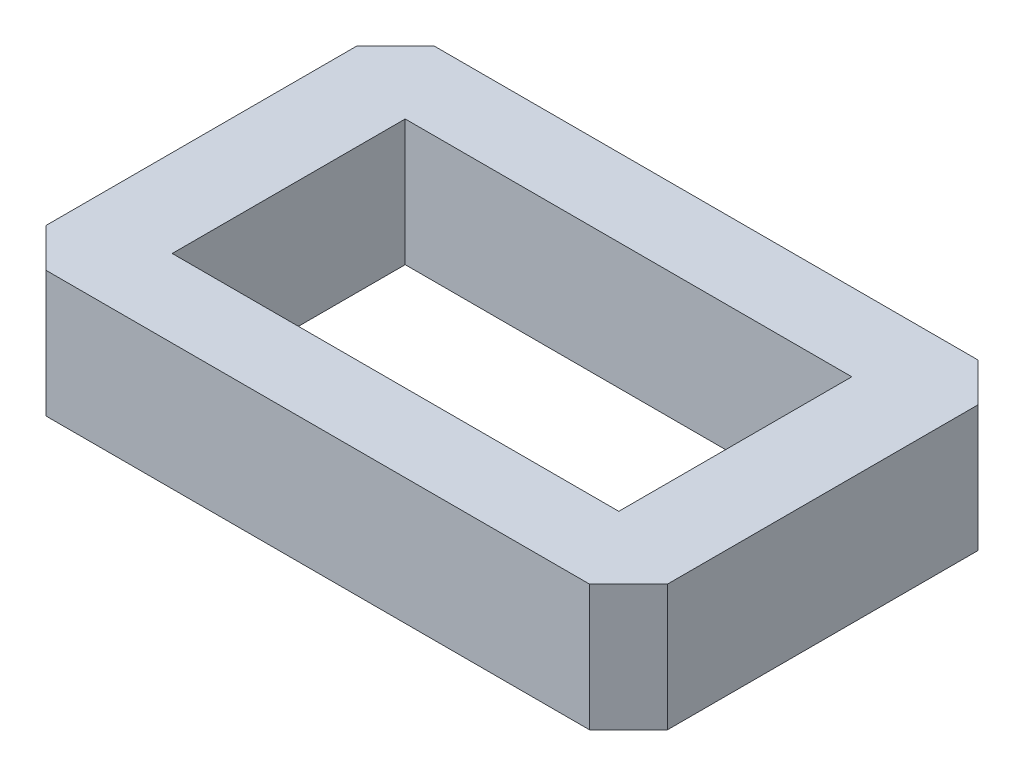
SolidWorks part; units mm, degrees
ref_plane "Front Plane" through (0, 0, 0) normal (0, 0, 1) x (1, 0, 0)
ref_plane "Top Plane" through (0, 0, 0) normal (0, 1, 0) x (1, 0, 0)
ref_plane "Right Plane" through (0, 0, 0) normal (1, 0, 0) x (0, 0, -1)
sketch "Sketch1" plane through (0, 0, 0) normal (0, 1, 0) x (1, 0, 0)
  line L1 (0, 0) -> (32, 0)
  line L2 (0, 0) -> (0, 20)
  line L3 (0, 20) -> (32, 20)
  line L4 (32, 0) -> (32, 20)
  dimension "D1" = 20
  dimension "D2" = 32
extrude "Boss-Extrude1" add sketch "Sketch1" along normal blind 6.5
sketch "Sketch2" plane through (0, 6.5, 0) normal (0, 1, 0) x (1, 0, 0)
  line L0 (16, 20) -> (16, 0)
  line L1 (32, 20) -> (0, 20) construction
  line L2 (0, 0) -> (32, 0) construction
  line L4 (4.5, 4) -> (27.5, 4)
  line L5 (4.5, 4) -> (4.5, 16)
  line L6 (4.5, 16) -> (27.5, 16)
  line L7 (27.5, 4) -> (27.5, 16)
  line L8 (4.5, 4) -> (27.5, 16) construction
  line L9 (4.5, 16) -> (27.5, 4) construction
  point P6 (16, 10)
  dimension "D1" = 12
  dimension "D2" = 23
extrude "Cut-Extrude1" cut sketch "Sketch2" against normal through all contours L6 L5 L4 L0 | L4 L7 L6 L0
chamfer "Chamfer1" distance 2 angle 45 4 edges at (32, 3.25, -20) (0, 3.25, -20) (0, 3.25, 0) (32, 3.25, 0)
